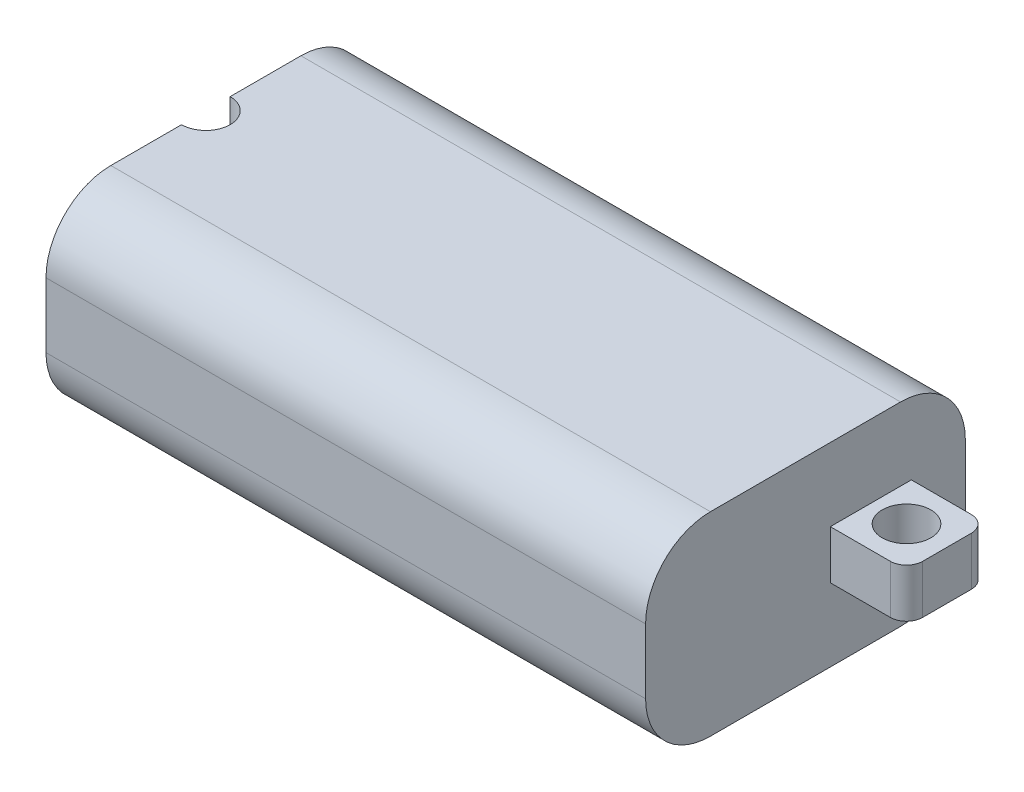
SolidWorks part; units mm, degrees
ref_plane "前视基准面" through (0, 0, 0) normal (0, 0, 1) x (1, 0, 0)
ref_plane "上视基准面" through (0, 0, 0) normal (0, 1, 0) x (1, 0, 0)
ref_plane "右视基准面" through (0, 0, 0) normal (1, 0, 0) x (0, 0, -1)
sketch "草图1" plane through (0, 0, 0) normal (0, 1, 0) x (1, 0, 0)
  line L1 (18.5, -9.865) -> (-18.5, -9.865)
  line L2 (18.5, -9.865) -> (18.5, 9.865)
  line L3 (18.5, 9.865) -> (-18.5, 9.865)
  line L4 (-18.5, -9.865) -> (-18.5, 9.865)
  line L5 (18.5, -9.865) -> (-18.5, 9.865) construction
  line L6 (18.5, 9.865) -> (-18.5, -9.865) construction
  point P0 (0, 0)
  dimension "D1" = 37
  dimension "D2" = 19.73
extrude "凸台-拉伸1" add sketch "草图1" along normal blind 12
sketch "草图2" plane through (0, 12, 0) normal (0, 1, 0) x (1, 0, 0)
  line L0 (-19.98, 0) -> (20.5684, 0) construction
  line L1 (-18.5, 9.865) -> (-18.5, -9.865) construction
  line L2 (-18.5, 9.865) -> (-18.5, -13.3612) construction
  circle A0 centre (-18.5, 0) radius 1.5
  dimension "D1" = 3
extrude "切除-拉伸1" cut sketch "草图2" against normal through all
fillet "圆角2" radius 4 4 edges at (0, 0, 9.865) (0, 12, 9.865) (0, 0, -9.865) (0, 12, -9.865)
sketch "草图3" plane through (-18.5, 0, 0) normal (-1, 0, 0) x (0, 0, 1)
  line L0 (-9.865, 6) -> (9.865, 6) construction
  line L1 (-9.865, 8) -> (-9.865, 4) construction
  line L2 (9.865, 8) -> (9.865, 4) construction
  circle A0 centre (-4.035, 6) radius 2.5
  dimension "D2" = 5
  dimension "D1" = 13.9
extrude "切除-拉伸2" cut sketch "草图3" against normal blind 30
sketch "草图4" plane through (18.5, 0, 0) normal (1, 0, 0) x (0, 0, -1)
  line L0 (-9.865, 6) -> (9.865, 6) construction
  line L1 (-9.865, 8) -> (-9.865, 4) construction
  line L2 (9.865, 8) -> (9.865, 4) construction
  line L4 (1.535, 4.5) -> (6.535, 4.5)
  line L5 (1.535, 4.5) -> (1.535, 7.5)
  line L6 (1.535, 7.5) -> (6.535, 7.5)
  line L7 (6.535, 4.5) -> (6.535, 7.5)
  line L8 (1.535, 4.5) -> (6.535, 7.5) construction
  line L9 (1.535, 7.5) -> (6.535, 4.5) construction
  point P6 (4.035, 6)
  dimension "D2" = 3
  dimension "D1" = 13.9
  dimension "D3" = 5
extrude "凸台-拉伸2" add sketch "草图4" along normal blind 4.7
sketch "草图5" plane through (0, 7.5, 0) normal (0, 1, 0) x (1, 0, 0)
  line L0 (23.2, 4.035) -> (18.5, 4.035) construction
  line L1 (23.2, 6.535) -> (23.2, 1.535) construction
  line L2 (18.5, 6.535) -> (18.5, 1.535) construction
  circle A0 centre (20.7, 4.035) radius 1.5
  dimension "D2" = 3
  dimension "D1" = 2.2
extrude "切除-拉伸3" cut sketch "草图5" against normal through all
fillet "圆角3" radius 1 2 edges at (23.2, 6, -1.535) (23.2, 6, -6.535)
